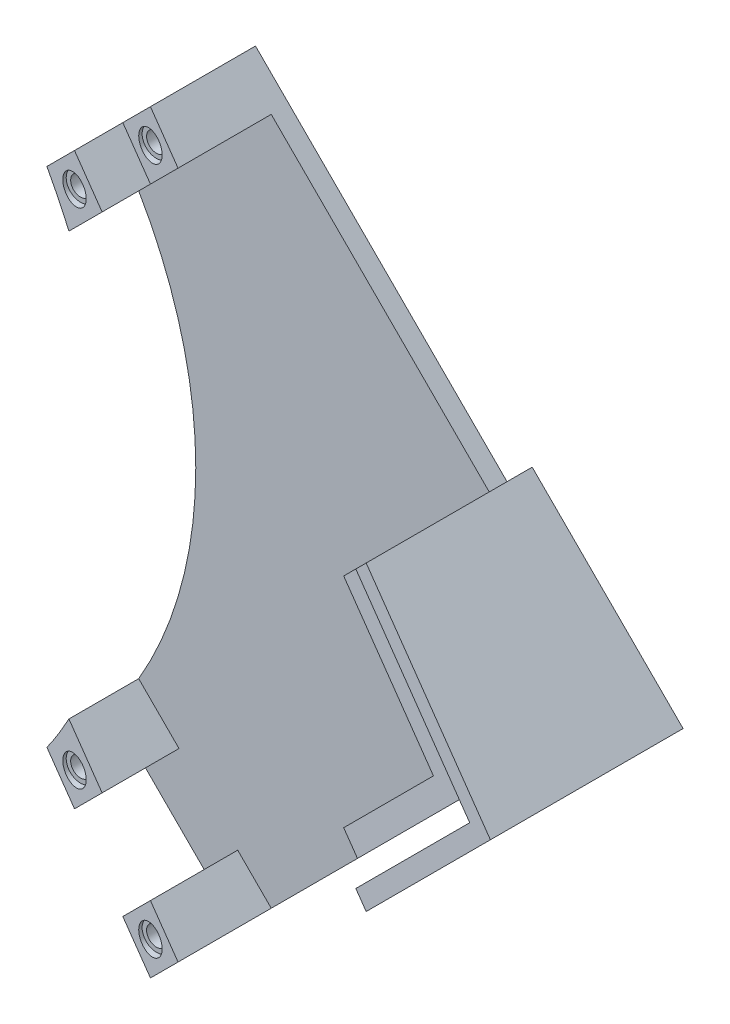
SolidWorks part; units mm, degrees
ref_plane "前视基准面" through (0, 0, 0) normal (0, 0, 1) x (1, 0, 0)
ref_plane "上视基准面" through (0, 0, 0) normal (0, 1, 0) x (1, 0, 0)
ref_plane "右视基准面" through (0, 0, 0) normal (1, 0, 0) x (0, 0, -1)
sketch "Closed_bottom_plate_3mm_sketch" plane through (0, 0, 0) normal (0, 0, 1) x (1, 0, 0)
  line L0 (77.7817, -63.6396) -> (141.4214, 0)
  line L1 (141.4214, 0) -> (77.7817, 63.6396)
  line L2 (77.7817, 63.6396) -> (56.5685, 42.4264)
  line L3 (56.5685, -42.4264) -> (77.7817, -63.6396)
  arc A0 (56.5685, 42.4264) -> (56.5685, -42.4264) centre (0, 0) cw
extrude "Closed_bottom_plate_3mm" add sketch "Closed_bottom_plate_3mm_sketch" along normal blind 3
sketch "Foot1_curved_R70p71_sketch" plane through (0, 0, 0) normal (0, 0, 1) x (1, 0, 0)
  line L0 (62.2254, 48.0833) -> (67.8823, 42.4264)
  line L1 (67.8823, 42.4264) -> (61.0808, 35.6249)
  line L2 (56.5685, 42.4264) -> (62.2254, 48.0833)
  arc A0 (61.0808, 35.6249) -> (56.5685, 42.4264) centre (0, 0) ccw
extrude "Foot1_curved_R70p71" add sketch "Foot1_curved_R70p71_sketch" along normal blind 33
sketch "Foot2_curved_R70p71_sketch" plane through (0, 0, 0) normal (0, 0, 1) x (1, 0, 0)
  line L0 (62.2254, -48.0833) -> (67.8823, -42.4264)
  line L1 (67.8823, -42.4264) -> (61.0808, -35.6249)
  line L2 (56.5685, -42.4264) -> (62.2254, -48.0833)
  arc A0 (61.0808, -35.6249) -> (56.5685, -42.4264) centre (0, 0) cw
extrude "Foot2_curved_R70p71" add sketch "Foot2_curved_R70p71_sketch" along normal blind 33
sketch "Pad4_C_blank_sketch" plane through (0, 0, 0) normal (0, 0, 1) x (1, 0, 0)
  line L0 (72.1249, 57.9828) -> (77.7817, 52.3259)
  line L1 (77.7817, 52.3259) -> (83.4386, 57.9828)
  line L2 (83.4386, 57.9828) -> (77.7817, 63.6396)
  line L3 (77.7817, 63.6396) -> (72.1249, 57.9828)
extrude "Pad4_C_blank" add sketch "Pad4_C_blank_sketch" along normal blind 33
sketch "Pad5_A_blank_sketch" plane through (0, 0, 0) normal (0, 0, 1) x (1, 0, 0)
  line L0 (72.1249, -57.9828) -> (77.7817, -63.6396)
  line L1 (77.7817, -63.6396) -> (83.4386, -57.9828)
  line L2 (83.4386, -57.9828) -> (77.7817, -52.3259)
  line L3 (77.7817, -52.3259) -> (72.1249, -57.9828)
extrude "Pad5_A_blank" add sketch "Pad5_A_blank_sketch" along normal blind 33
sketch "Slot_backing_inside_north_sketch" plane through (0, 0, 0) normal (0, 0, 1) x (1, 0, 0)
  line L0 (117.3797, 18.3848) -> (138.5929, -2.8284)
  line L1 (138.5929, -2.8284) -> (141.4214, 0)
  line L2 (141.4214, 0) -> (120.2082, 21.2132)
  line L3 (120.2082, 21.2132) -> (117.3797, 18.3848)
extrude "Slot_backing_inside_north" add sketch "Slot_backing_inside_north_sketch" along normal blind 35
sketch "Slot_backing_inside_east_sketch" plane through (0, 0, 0) normal (0, 0, 1) x (1, 0, 0)
  line L0 (117.3797, -18.3848) -> (120.2082, -21.2132)
  line L1 (120.2082, -21.2132) -> (141.4214, 0)
  line L2 (141.4214, 0) -> (138.5929, 2.8284)
  line L3 (138.5929, 2.8284) -> (117.3797, -18.3848)
extrude "Slot_backing_inside_east" add sketch "Slot_backing_inside_east_sketch" along normal blind 35
sketch "Top_outer_plane_sketch" plane through (0, 0, 0) normal (0, 1, 0) x (1, 0, 0)
  line L0 (-100, 13.7087) -> (250, -48.1632)
  line L1 (250, -48.1632) -> (250, -100)
  line L2 (250, -100) -> (-100, -100)
  line L3 (-100, -100) -> (-100, 13.7087)
extrude "Top_outer_plane" cut sketch "Top_outer_plane_sketch" against normal through all and the other way through all
sketch "Slot_base_north_sketch" plane through (0, 0, 0) normal (0, 0, 1) x (1, 0, 0)
  line L0 (117.3797, 18.3848) -> (142.8356, -7.0711)
  line L1 (142.8356, -7.0711) -> (149.9066, 0)
  line L2 (149.9066, 0) -> (124.4508, 25.4558)
  line L3 (124.4508, 25.4558) -> (117.3797, 18.3848)
extrude "Slot_base_north" add sketch "Slot_base_north_sketch" along normal blind 3
sketch "Slot_base_east_sketch" plane through (0, 0, 0) normal (0, 0, 1) x (1, 0, 0)
  line L0 (117.3797, -18.3848) -> (124.4508, -25.4558)
  line L1 (124.4508, -25.4558) -> (149.9066, 0)
  line L2 (149.9066, 0) -> (142.8356, 7.0711)
  line L3 (142.8356, 7.0711) -> (117.3797, -18.3848)
extrude "Slot_base_east" add sketch "Slot_base_east_sketch" along normal blind 3
sketch "Slot_outer_north_sketch" plane through (0, 0, 0) normal (0, 0, 1) x (1, 0, 0)
  line L0 (122.3295, 23.3345) -> (147.7853, -2.1213)
  line L1 (147.7853, -2.1213) -> (149.9066, 0)
  line L2 (149.9066, 0) -> (124.4508, 25.4558)
  line L3 (124.4508, 25.4558) -> (122.3295, 23.3345)
extrude "Slot_outer_north" add sketch "Slot_outer_north_sketch" along normal blind 35
sketch "Slot_outer_east_sketch" plane through (0, 0, 0) normal (0, 0, 1) x (1, 0, 0)
  line L0 (122.3295, -23.3345) -> (124.4508, -25.4558)
  line L1 (124.4508, -25.4558) -> (149.9066, 0)
  line L2 (149.9066, 0) -> (147.7853, 2.1213)
  line L3 (147.7853, 2.1213) -> (122.3295, -23.3345)
extrude "Slot_outer_east" add sketch "Slot_outer_east_sketch" along normal blind 35
sketch "草图13" plane through (0, 0, 0) normal (0, 1, 0) x (1, 0, 0)
  line L0 (-100, 11.6777) -> (250, -50.1942)
  line L1 (250, -50.1942) -> (250, -100)
  line L2 (250, -100) -> (-100, -100)
  line L3 (-100, -100) -> (-100, 11.6777)
extrude "切除-拉伸2" cut sketch "草图13" against normal through all and the other way through all
sketch "Locator_1_socket_D3p3_sketch" plane through (0, 0, 0) normal (0, 0, 1) x (1, 0, 0)
  circle A0 centre (62.2254, 42.4264) radius 1.65
extrude "Locator_1_socket_D3p3" cut sketch "Locator_1_socket_D3p3_sketch" along normal blind 7 from offset 9.969
sketch "Locator_1_root_relief_D4p8_sketch" plane through (0, 0, 0) normal (0, 0, 1) x (1, 0, 0)
  circle A0 centre (62.2254, 42.4264) radius 2.4
extrude "Locator_1_root_relief_D4p8" cut sketch "Locator_1_root_relief_D4p8_sketch" along normal blind 3 from offset 13.969
sketch "Locator_2_socket_D3p3_sketch" plane through (0, 0, 0) normal (0, 0, 1) x (1, 0, 0)
  circle A0 centre (62.2254, -42.4264) radius 1.65
extrude "Locator_2_socket_D3p3" cut sketch "Locator_2_socket_D3p3_sketch" along normal blind 7 from offset 9.969
sketch "Locator_2_root_relief_D4p8_sketch" plane through (0, 0, 0) normal (0, 0, 1) x (1, 0, 0)
  circle A0 centre (62.2254, -42.4264) radius 2.4
extrude "Locator_2_root_relief_D4p8" cut sketch "Locator_2_root_relief_D4p8_sketch" along normal blind 3 from offset 13.969
sketch "Locator_3_socket_D3p3_sketch" plane through (0, 0, 0) normal (0, 0, 1) x (1, 0, 0)
  circle A0 centre (77.7817, 57.9828) radius 1.65
extrude "Locator_3_socket_D3p3" cut sketch "Locator_3_socket_D3p3_sketch" along normal blind 7 from offset 12.719
sketch "Locator_3_root_relief_D4p8_sketch" plane through (0, 0, 0) normal (0, 0, 1) x (1, 0, 0)
  circle A0 centre (77.7817, 57.9828) radius 2.4
extrude "Locator_3_root_relief_D4p8" cut sketch "Locator_3_root_relief_D4p8_sketch" along normal blind 3 from offset 16.719
sketch "Locator_4_socket_D3p3_sketch" plane through (0, 0, 0) normal (0, 0, 1) x (1, 0, 0)
  circle A0 centre (77.7817, -57.9828) radius 1.65
extrude "Locator_4_socket_D3p3" cut sketch "Locator_4_socket_D3p3_sketch" along normal blind 7 from offset 12.719
sketch "Locator_4_root_relief_D4p8_sketch" plane through (0, 0, 0) normal (0, 0, 1) x (1, 0, 0)
  circle A0 centre (77.7817, -57.9828) radius 2.4
extrude "Locator_4_root_relief_D4p8" cut sketch "Locator_4_root_relief_D4p8_sketch" along normal blind 3 from offset 16.719
